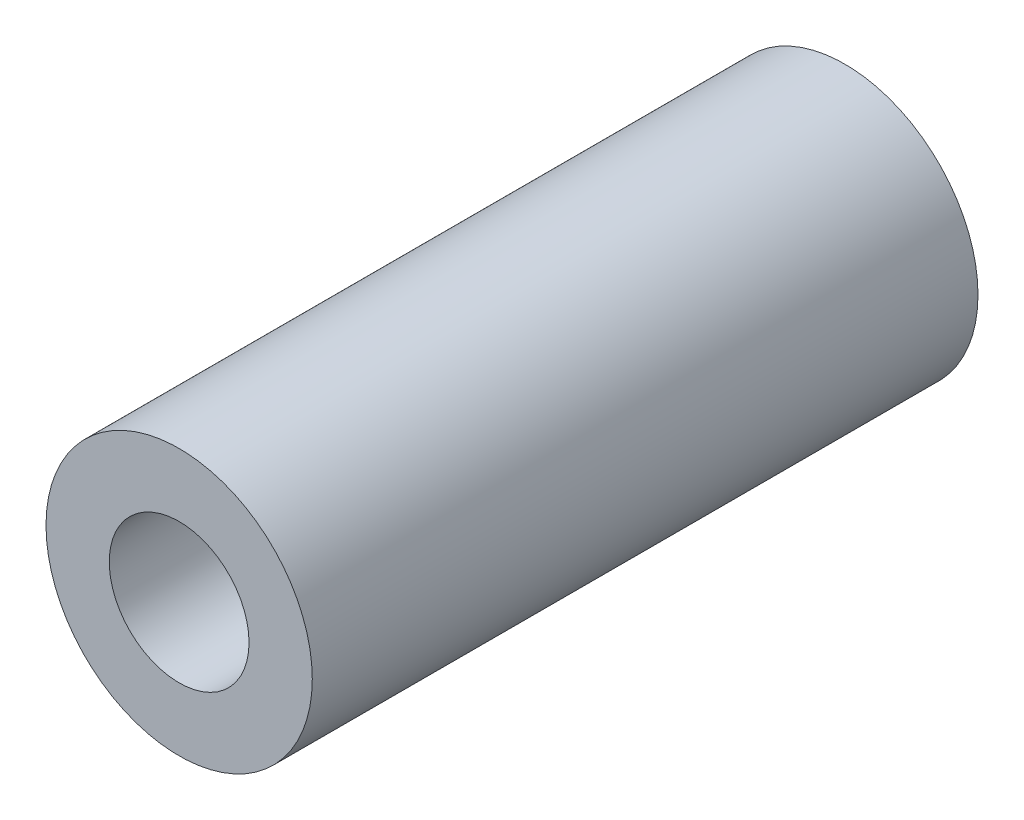
SolidWorks part; units mm, degrees
material "ASTM A36 Steel"
ref_plane "Front Plane" through (0, 0, 0) normal (0, 0, 1) x (1, 0, 0)
ref_plane "Top Plane" through (0, 0, 0) normal (0, 1, 0) x (1, 0, 0)
ref_plane "Right Plane" through (0, 0, 0) normal (1, 0, 0) x (0, 0, -1)
sketch "Sketch1" plane through (0, 0, 0) normal (0, 0, 1) x (1, 0, 0)
  circle A0 centre (0, 0) radius 10
  circle A1 centre (0, 0) radius 5.25
  dimension "D1" = 20
  dimension "D2" = 10.5
extrude "Boss-Extrude1" add sketch "Sketch1" along normal blind 50
